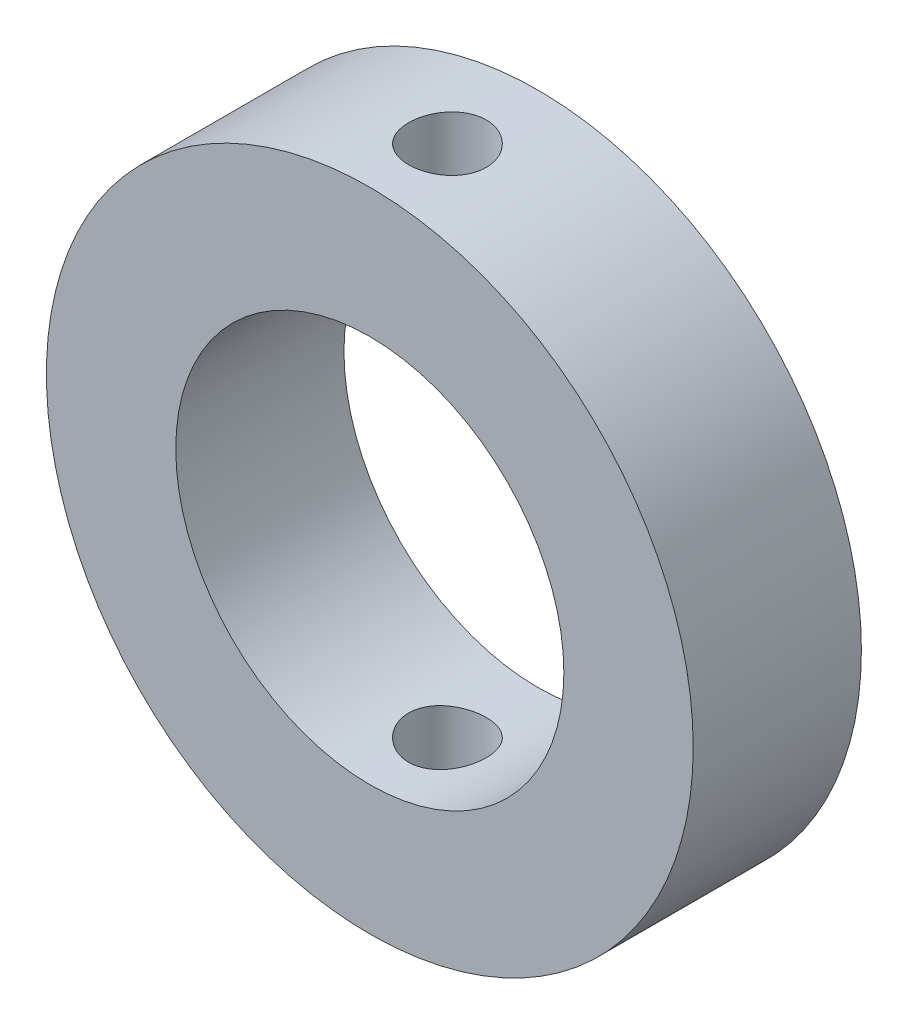
SolidWorks part; units mm, degrees
ref_plane "Front Plane" through (0, 0, 0) normal (0, 0, 1) x (1, 0, 0)
ref_plane "Top Plane" through (0, 0, 0) normal (0, 1, 0) x (1, 0, 0)
ref_plane "Right Plane" through (0, 0, 0) normal (1, 0, 0) x (0, 0, -1)
sketch "Sketch1" plane through (0, 0, 0) normal (0, 0, 1) x (1, 0, 0)
  circle A0 centre (0, 0) radius 25
  circle A1 centre (0, 0) radius 15
  point P4 (-213.9385, -62.9569)
extrude "Boss-Extrude1" add sketch "Sketch1" along normal blind 13
sketch "Sketch2" plane through (0, 0, 0) normal (0, 1, 0) x (1, 0, 0)
  circle A0 centre (0, -7) radius 3
extrude "Cut-Extrude1" cut sketch "Sketch2" against normal mid plane 83 contours A0
